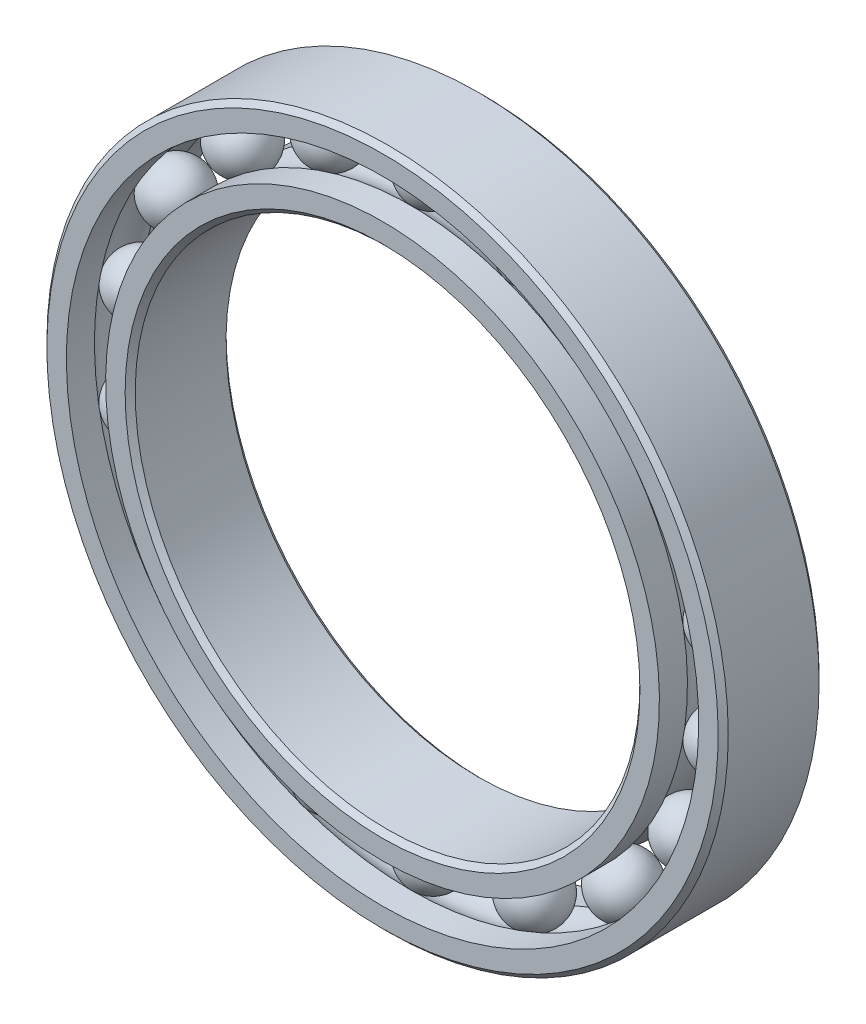
SolidWorks part; units mm, degrees
ref_plane "Front Plane" through (0, 0, 0) normal (0, 0, 1) x (1, 0, 0)
ref_plane "Top Plane" through (0, 0, 0) normal (0, 1, 0) x (1, 0, 0)
ref_plane "Right Plane" through (0, 0, 0) normal (1, 0, 0) x (0, 0, -1)
sketch "Sketch1" plane through (0, 0, 0) normal (0, 0, 1) x (1, 0, 0)
  circle A0 centre (0, 0) radius 13.5
  circle A1 centre (0, 0) radius 10
  dimension "OD" = 27
  dimension "ID" = 20
  dimension "For Shaft Diameter" = 20
  dimension "For Housing ID" = 27
sketch "Sketch5" plane through (0, 0, 0) normal (1, 0, 0) x (0, 0, -1)
  line L0 (-2, 0) -> (2, 0) construction
  line L1 (0, 13.5) -> (0, -13.5) construction
  line L2 (1.8, 13.5) -> (-1.8, 13.5)
  line L3 (-1.8, 13.5) -> (-2, 13.3)
  line L4 (-2, 13.3) -> (-2, 12.5278)
  line L5 (-2, 12.5278) -> (-0.8889, 12.5278)
  line L6 (2, 12.5278) -> (0.8889, 12.5278)
  line L7 (2, 13.3) -> (2, 12.5278)
  line L8 (1.8, 13.5) -> (2, 13.3)
  line L9 (0, 13.5) -> (0, 11.75) construction
  line L10 (0, 11.75) -> (0, 10) construction
  line L11 (-1.1811, 11.75) -> (-2, 11.75) construction
  line L12 (1.4001, 10.9976) -> (1.7811, 10.9976) construction
  line L13 (-1.4001, 10.9976) -> (-1.7811, 10.9976) construction
  line L14 (-1.4001, 10.9976) -> (-1.4001, 12.5024) construction
  line L15 (-1.4001, 12.5024) -> (-1.7811, 12.5024) construction
  line L16 (-1.7811, 10.9976) -> (-1.7811, 12.5024) construction
  line L17 (-1.4001, 10.9976) -> (-1.7811, 12.5024) construction
  line L18 (-1.4001, 12.5024) -> (-1.7811, 10.9976) construction
  line L19 (1.7811, 10.9976) -> (1.7811, 12.5024) construction
  line L20 (1.4001, 12.5024) -> (1.7811, 12.5024) construction
  line L21 (1.4001, 10.9976) -> (1.4001, 12.5024) construction
  line L22 (0, 13.5) -> (0, -13.5) construction
  arc A0 (-0.8889, 12.5278) -> (0.8889, 12.5278) centre (0, 11.75) cw
  circle A1 centre (0, 11.75) radius 1.1811 construction
  point P14 (0, 10)
  point P15 (-1.5906, 11.75)
  dimension "D1" = 45
  dimension "D2" = 0.2
  dimension "D3" = 1.7778
  dimension "D4" = 0.7778
  dimension "D5" = 0.381
  dimension "D6" = 0.0254
  dimension "Width" = 4
sketch "Sketch6" plane through (0, 0, 0) normal (1, 0, 0) x (0, 0, -1)
  line L0 (1.8, 13.5) -> (2, 13.3) construction
  line L1 (2, 13.3) -> (2, 12.5278) construction
  line L2 (2, 12.5278) -> (0.8889, 12.5278) construction
  line L3 (-2, 12.5278) -> (-0.8889, 12.5278) construction
  line L4 (-2, 13.3) -> (-2, 12.5278) construction
  line L5 (-1.8, 13.5) -> (-2, 13.3) construction
  line L6 (1.8, 13.5) -> (-1.8, 13.5) construction
  line L7 (1.8, 13.5) -> (2, 13.3)
  line L8 (2, 13.3) -> (2, 12.5278)
  line L9 (2, 12.5278) -> (0.8889, 12.5278)
  line L10 (-2, 12.5278) -> (-0.8889, 12.5278)
  line L11 (-2, 13.3) -> (-2, 12.5278)
  line L12 (-1.8, 13.5) -> (-2, 13.3)
  line L13 (1.8, 13.5) -> (-1.8, 13.5)
  arc A0 (0.8889, 12.5278) -> (-0.8889, 12.5278) centre (0, 11.75) ccw construction
  arc A1 (0.8889, 12.5278) -> (-0.8889, 12.5278) centre (0, 11.75) ccw
revolve "Revolve5" add sketch "Sketch6" angle 360 about L0
sketch "Sketch3" plane through (0, 0, 0) normal (1, 0, 0) x (0, 0, -1)
  line L0 (-2, 10.9722) -> (-0.8889, 10.9722)
  line L1 (0, 13.5) -> (0, -13.5) construction
  line L2 (-2, 13.3) -> (-2, 12.5278) construction
  line L3 (-2, 10.9722) -> (-2, 10.2)
  line L4 (-1.8, 13.5) -> (-2, 13.3) construction
  line L5 (-2, 10.2) -> (-1.8, 10)
  line L6 (-1.8, 10) -> (1.8, 10)
  line L8 (1.8, 10) -> (2, 10.2)
  line L10 (2, 10.2) -> (2, 10.9722)
  line L11 (2, 10.9722) -> (0.8889, 10.9722)
  line L12 (1.8, 13.5) -> (1.8, -13.5) construction
  line L13 (1.8, 13.5) -> (2, 13.3) construction
  line L14 (2, -13.3) -> (2, 13.3) construction
  arc A0 (0.8889, 12.5278) -> (-0.8889, 12.5278) centre (0, 11.75) ccw construction
  arc A1 (0.8889, 10.9722) -> (-0.8889, 10.9722) centre (0, 11.75) cw
revolve "Revolve3" add sketch "Sketch3" angle 360 about L0
sketch "Sketch4" plane through (0, 0, 0) normal (1, 0, 0) x (0, 0, -1)
  line L0 (-1.1811, 11.75) -> (1.1811, 11.75)
  arc A2 (-1.1811, 11.75) -> (1.1811, 11.75) centre (0, 11.75) cw
  arc A3 (0.8889, 12.5278) -> (-0.8889, 12.5278) centre (0, 11.75) ccw construction
revolve "Revolve4" add sketch "Sketch4" angle 360 about L0
pattern_circular "CirPattern1" count 18 over 360 about axis through (0, 0, 0) along (0, 0, 1) of bodies 104
equation "\"D2@Sketch5\" = \"Width@Sketch5\" * .05"
equation "\"D3@Sketch5\" = \"Width@Sketch5\" / 2.25"
equation "\"D4@Sketch5\"=((\"OD@Sketch1\"-\"ID@Sketch1\")/2)/4.5"
